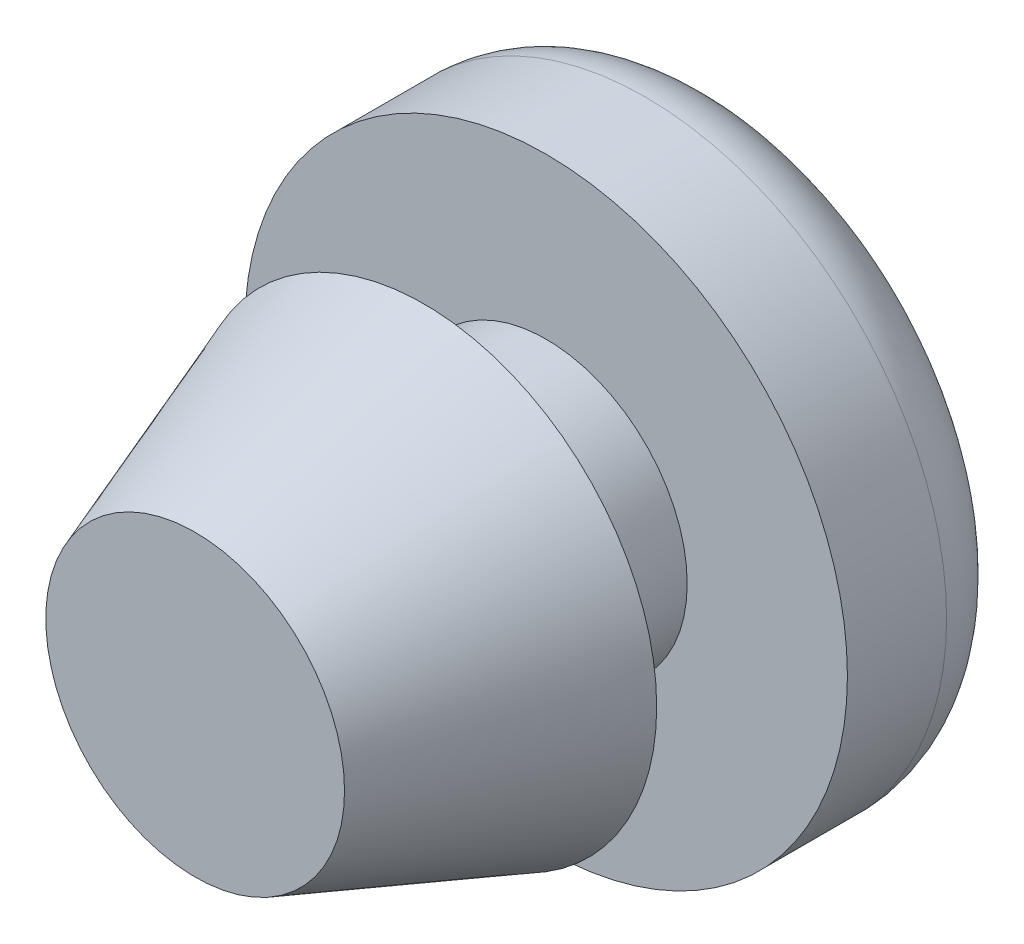
SolidWorks part; units mm, degrees
material "冷轧钢板"
ref_plane "前视基准面" through (0, 0, 0) normal (0, 0, 1) x (1, 0, 0)
ref_plane "上视基准面" through (0, 0, 0) normal (0, 1, 0) x (1, 0, 0)
ref_plane "右视基准面" through (0, 0, 0) normal (1, 0, 0) x (0, 0, -1)
sketch "草图1" plane through (0, 0, 0) normal (0, 0, 1) x (1, 0, 0)
  circle A0 centre (0, 0) radius 3.95
  dimension "D1" = 7.9
extrude "凸台-拉伸1" add sketch "草图1" along normal blind 2.3
sketch "草图2" plane through (0, 0, 2.3) normal (0, 0, 1) x (1, 0, 0)
  circle A0 centre (0, 0) radius 1.85
  dimension "D1" = 3.7
extrude "凸台-拉伸2" add sketch "草图2" along normal blind 1.6
sketch "草图3" plane through (0, 0, 3.9) normal (0, 0, 1) x (1, 0, 0)
  circle A0 centre (0, 0) radius 3.05
  dimension "D1" = 6.1
extrude "凸台-拉伸3" add sketch "草图3" along normal blind 3
draft "拔模7" type of draft neutral plane draft angle 20 faces to draft 1 face at (3.05, 0, 6.9) neutral plane through (0, 0, 3.9) neutral plane normal (0, 0, -1) reverse direction yes parameters "D1"=20
fillet "圆角1" radius 1 1 edges at (3.95, 0, 0)
